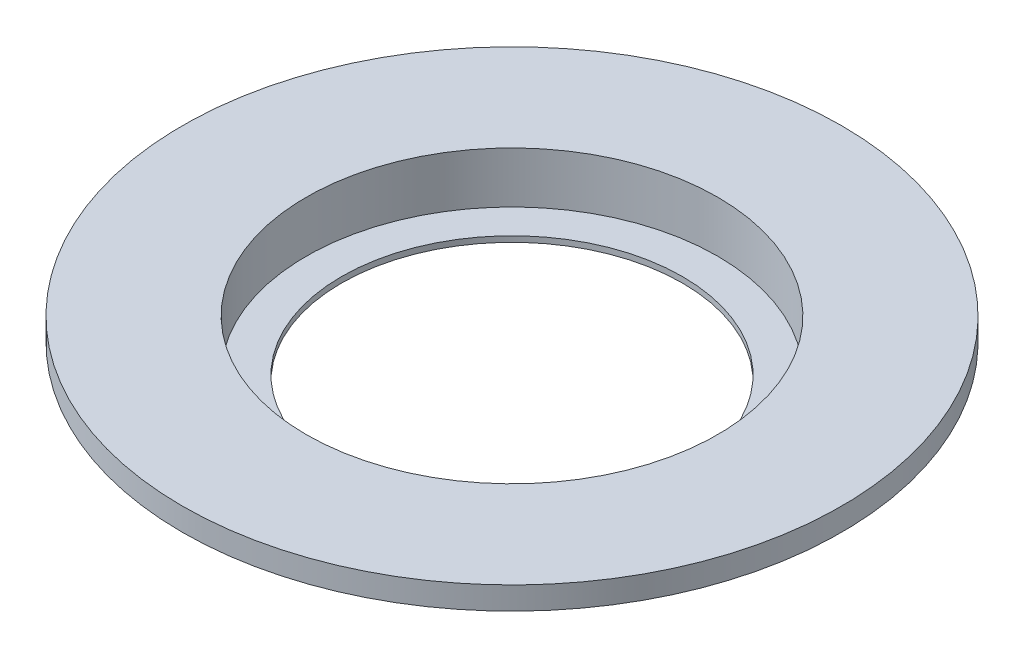
SolidWorks part; units mm, degrees
ref_plane "Front Plane" through (0, 0, 0) normal (0, 0, 1) x (1, 0, 0)
ref_plane "Top Plane" through (0, 0, 0) normal (0, 1, 0) x (1, 0, 0)
ref_plane "Right Plane" through (0, 0, 0) normal (1, 0, 0) x (0, 0, -1)
sketch "Sketch3" plane through (0, 0, 0) normal (0, 1, 0) x (1, 0, 0)
  circle A1 centre (0, 0) radius 37.2
  dimension "D2" = 74.4
extrude "Boss-Extrude1" add sketch "Sketch3" along normal blind 10
sketch "Sketch4" plane through (0, 10, 0) normal (0, 1, 0) x (1, 0, 0)
  circle A0 centre (0, 0) radius 36.2
  dimension "D1" = 72.4
extrude "Cut-Extrude1" cut sketch "Sketch4" against normal blind 9
sketch "Sketch5" plane through (0, 1, 0) normal (0, 1, 0) x (1, 0, 0)
  circle A0 centre (0, 0) radius 30
  dimension "D1" = 60
extrude "Cut-Extrude2" cut sketch "Sketch5" against normal blind 9
ref_plane "Plane1" through (0, 6, 0) normal (0, 1, 0) x (1, 0, 0)
sketch "Sketch6" plane through (0, 6, 0) normal (0, 1, 0) x (1, 0, 0)
  circle A0 centre (0, 0) radius 58
  circle A1 centre (0, 0) radius 37.2
  dimension "D1" = 116
extrude "Boss-Extrude2" add sketch "Sketch6" along normal blind 4
sketch "Sketch7" plane through (0, 6, 0) normal (0, -1, 0) x (1, 0, 0)
  circle A0 centre (0, 0) radius 47.8
  circle A1 centre (0, 0) radius 46.5
  dimension "D1" = 95.6
  dimension "D2" = 93
extrude "Boss-Extrude3" add sketch "Sketch7" along normal blind 3
